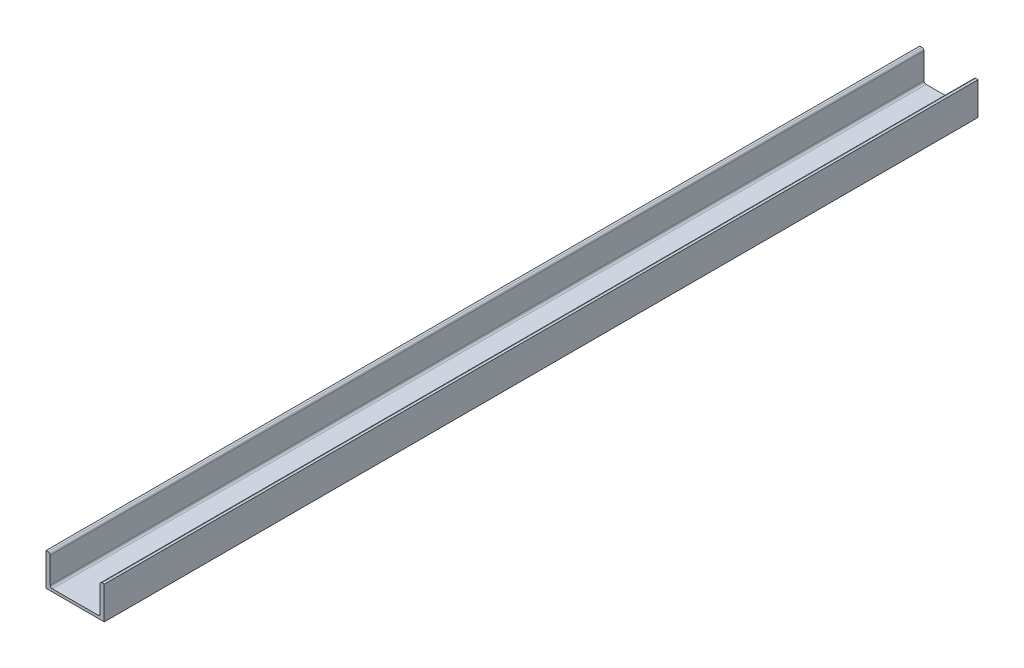
SolidWorks part; units mm, degrees
ref_plane "Front Plane" through (0, 0, 0) normal (0, 0, 1) x (1, 0, 0)
ref_plane "Top Plane" through (0, 0, 0) normal (0, 1, 0) x (1, 0, 0)
ref_plane "Right Plane" through (0, 0, 0) normal (1, 0, 0) x (0, 0, -1)
sketch "Sketch1" plane through (0, 0, 0) normal (0, 0, 1) x (1, 0, 0)
  line L0 (-50.8, 28.575) -> (-50.8, -28.575) construction
  line L1 (-50.8, -28.575) -> (50.8, -28.575) construction
  line L2 (50.8, -28.575) -> (50.8, 28.575) construction
  line L3 (43.434, -23.749) -> (-43.434, -23.749) construction
  line L4 (-43.434, -23.749) -> (-43.434, 28.575) construction
  line L6 (-43.434, 28.575) -> (-50.8, 28.575) construction
  line L7 (0, -28.575) -> (0, 0) construction
  line L8 (50.8, 28.575) -> (43.434, 28.575) construction
  line L9 (43.434, 28.575) -> (43.434, -23.749) construction
  line L10 (0, -23.749) -> (0, -28.575) construction
  point P4 (0, 0)
  point P11 (50.8, -23.749)
  dimension "Outside Height" = 57.15
  dimension "Outside Width" = 101.6
  dimension "Leg Thickness" = 7.366
  dimension "D1" = 28.575
  dimension "Inside Height" = 52.324
  dimension "Inside Width" = 86.868
  dimension "Base Thickness" = 4.826
sketch "Sketch2" plane through (0, 0, 0) normal (1, 0, 0) x (0, 0, -1)
  line L0 (762, 28.575) -> (-762, 28.575) construction
  line L1 (0, -23.749) -> (0, 28.575) construction
  point P0 (-635, 28.575)
  point P4 (0, 28.575)
  point P6 (635, 28.575)
  dimension "D1" = 127
  dimension "D2" = 127
  dimension "Length" = 1524
sketch "Sketch3" plane through (0, 0, 0) normal (0, 0, 1) x (1, 0, 0)
  line L6 (-50.8, 28.575) -> (-50.8, -28.575)
  line L7 (-50.8, -28.575) -> (50.8, -28.575)
  line L8 (50.8, -28.575) -> (50.8, 28.575)
  line L9 (50.8, 28.575) -> (43.434, 28.575)
  line L10 (43.434, 28.575) -> (43.434, -23.749)
  line L11 (43.434, -23.749) -> (-43.434, -23.749)
  line L12 (-43.434, -23.749) -> (-43.434, 28.575)
  line L13 (-43.434, 28.575) -> (-50.8, 28.575)
extrude "Boss-Extrude1" add sketch "Sketch3" along normal mid plane 1524
fillet "Fillet1" radius 3.683 4 edges at (-43.434, 28.575, 0) (43.434, 28.575, 0) (43.434, -23.749, 0) (-43.434, -23.749, 0)
equation "\"D1@Boss-Extrude1\"=\"Length@Sketch2\""
equation "\"D2@Sketch2\"=\"D1@Sketch2\""
equation "\"D1@Sketch1\"=\"Outside Height@Sketch1\"/2"
equation "\"D1@Fillet1\"=\"Leg Thickness@Sketch1\"*.5"
equation "\"D1@Sketch2\"=\"Outside Width@Sketch1\"*1.25"
